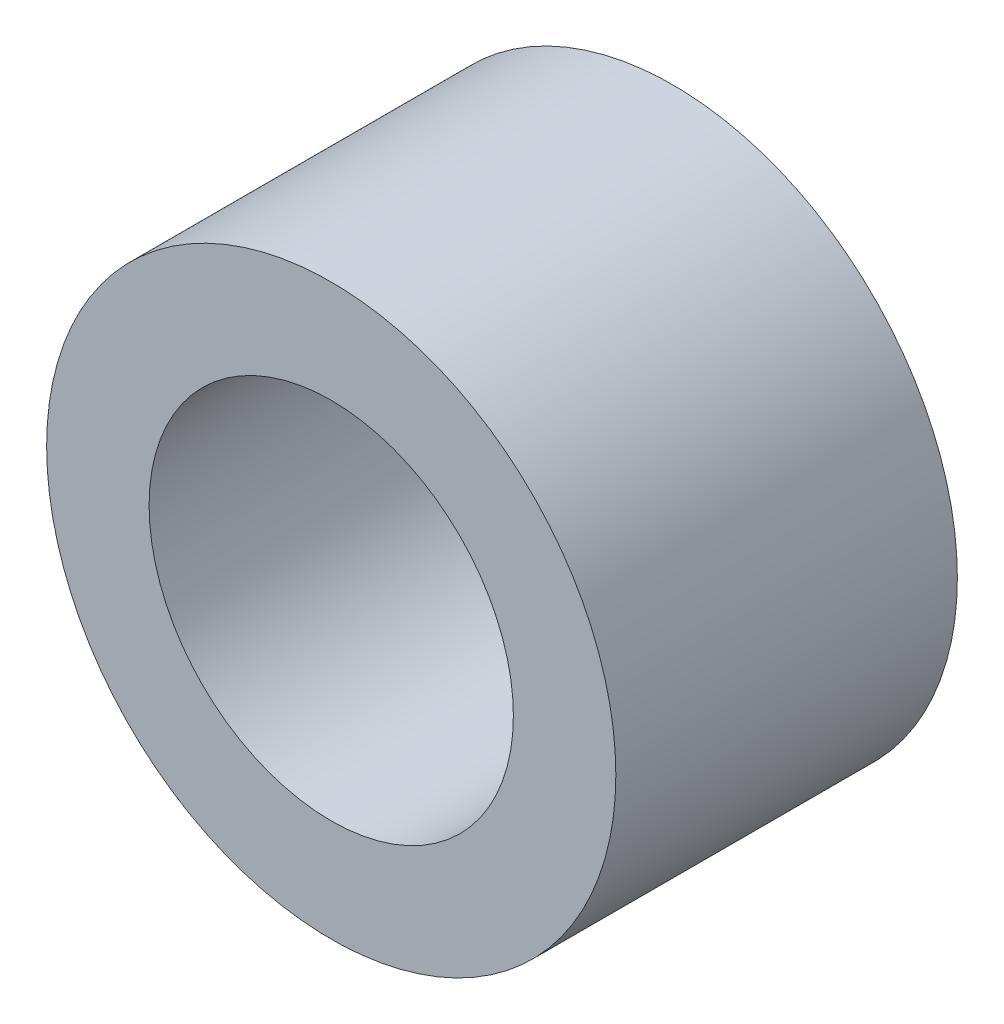
SolidWorks part; units mm, degrees
material "ﾎﾟﾘｴｽﾃﾙ樹脂"
ref_plane "正面" through (0, 0, 0) normal (0, 0, 1) x (1, 0, 0)
ref_plane "平面" through (0, 0, 0) normal (0, 1, 0) x (1, 0, 0)
ref_plane "右側面" through (0, 0, 0) normal (1, 0, 0) x (0, 0, -1)
sketch "ｽｹｯﾁ1" plane through (0, 0, 0) normal (0, 0, 1) x (1, 0, 0)
  circle A0 centre (0, 0) radius 2.5
  circle A1 centre (0, 0) radius 1.6
  dimension "D1" = 3.2
  dimension "D2" = 5
extrude "ﾎﾞｽ - 押し出し1" add sketch "ｽｹｯﾁ1" along normal blind 3
